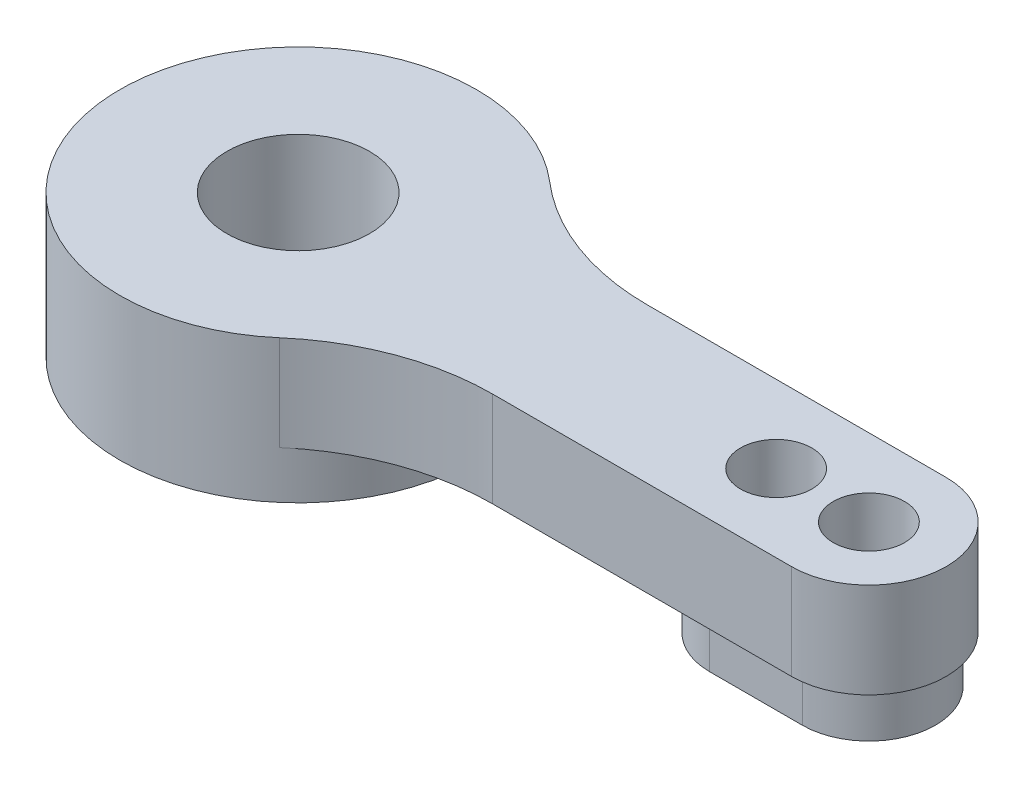
SolidWorks part; units mm, degrees
material "Nickel"
ref_plane "Front Plane" through (0, 0, 0) normal (0, 0, 1) x (1, 0, 0)
ref_plane "Top Plane" through (0, 0, 0) normal (0, 1, 0) x (1, 0, 0)
ref_plane "Right Plane" through (0, 0, 0) normal (1, 0, 0) x (0, 0, -1)
sketch "Sketch1" plane through (0, 0, 0) normal (0, 1, 0) x (1, 0, 0)
  circle A0 centre (0, 0) radius 7.5
  dimension "D1" = 15
extrude "Boss-Extrude1" add sketch "Sketch1" along normal blind 6
sketch "Sketch2" plane through (0, 6, 0) normal (0, 1, 0) x (1, 0, 0)
  line L0 (0, 0) -> (24, 0) construction
  line L1 (0, 3.25) -> (24, 3.25)
  line L2 (0, -3.25) -> (24, -3.25)
  arc A0 (0, 3.25) -> (0, -3.25) centre (0, 0) ccw
  arc A1 (24, -3.25) -> (24, 3.25) centre (24, 0) ccw
  point P3 (12, 0)
  dimension "D1" = 24
  dimension "D2" = 6.5
extrude "Boss-Extrude2" add sketch "Sketch2" against normal blind 4
sketch "Sketch4" plane through (0, 2, 0) normal (0, -1, 0) x (-1, 0, 0)
  line L0 (-24, 0) -> (-20.1, 0) construction
  line L1 (-24, 2.8) -> (-20.1, 2.8)
  line L2 (-24, -2.8) -> (-20.1, -2.8)
  arc A0 (-24, 2.8) -> (-24, -2.8) centre (-24, 0) ccw
  arc A1 (-20.1, -2.8) -> (-20.1, 2.8) centre (-20.1, 0) ccw
  point P4 (-22.05, 0)
  dimension "D1" = 3.9
  dimension "D2" = 2.8
extrude "Boss-Extrude3" add sketch "Sketch4" along normal blind 2
sketch "Sketch5" plane through (0, 0, 0) normal (0, -1, 0) x (1, 0, 0)
  circle A0 centre (24, 0) radius 1.5
  circle A1 centre (20.1, 0) radius 1.5
  circle A2 centre (0, 0) radius 3
  dimension "D1" = 3
  dimension "D2" = 6
extrude "Cut-Extrude1" cut sketch "Sketch5" against normal through all both and the other way through all
fillet "Fillet1" radius 10 2 edges at (6.7593, 4, -3.25) (6.7593, 4, 3.25)
